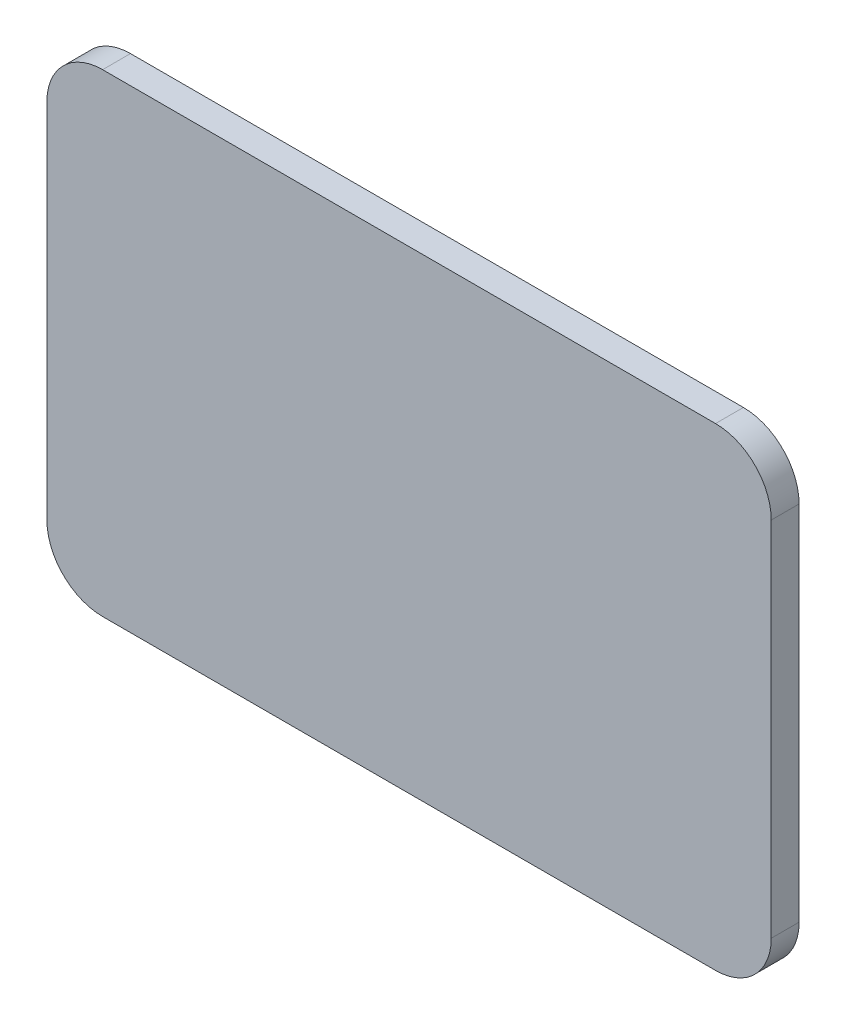
SolidWorks part; units mm, degrees
ref_plane "前视基准面" through (0, 0, 0) normal (0, 0, 1) x (1, 0, 0)
ref_plane "上视基准面" through (0, 0, 0) normal (0, 1, 0) x (1, 0, 0)
ref_plane "右视基准面" through (0, 0, 0) normal (1, 0, 0) x (0, 0, -1)
other "Configuration Table"
sketch "草图1" plane through (0, 0, 0) normal (0, 0, 1) x (1, 0, 0)
  line L0 (0, 0) -> (26, 0)
  line L1 (26, 0) -> (26, 17)
  line L2 (26, 17) -> (0, 17)
  line L3 (0, 17) -> (0, 0)
  dimension "width" = 26
  dimension "height" = 17
extrude "BlockExtrude" add sketch "草图1" along normal blind 1
fillet "Fillet" radius 2 4 edges at (0, 17, 0.5) (26, 17, 0.5) (26, 0, 0.5) (0, 0, 0.5)
